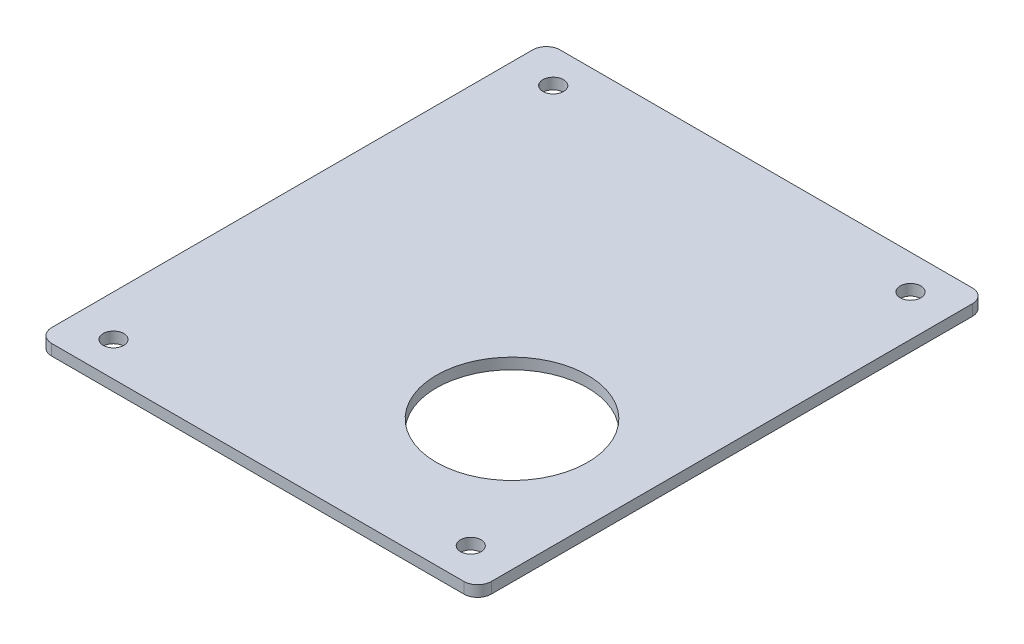
SolidWorks part; units mm, degrees
material "A-玻璃纤维"
ref_plane "前视基准面" through (0, 0, 0) normal (0, 0, 1) x (1, 0, 0)
ref_plane "上视基准面" through (0, 0, 0) normal (0, 1, 0) x (1, 0, 0)
ref_plane "右视基准面" through (0, 0, 0) normal (1, 0, 0) x (0, 0, -1)
other "Configuration Table"
sketch "草图1" plane through (0, 0, 0) normal (0, 1, 0) x (1, 0, 0)
  line L0 (0, 0) -> (0, 33.5742) construction
  line L1 (-32, -37) -> (32, -37)
  line L2 (-32, -37) -> (-32, 37)
  line L3 (-32, 37) -> (32, 37)
  line L4 (32, -37) -> (32, 37)
  line L5 (-32, -37) -> (32, 37) construction
  line L6 (-32, 37) -> (32, -37) construction
  line L7 (0, 0) -> (44.1006, 0) construction
  circle A0 centre (26, 32) radius 1.5
  circle A3 centre (-26, 32) radius 1.5
  circle A4 centre (13, -13) radius 11
  circle A5 centre (26, -32) radius 1.5
  circle A6 centre (-26, -32) radius 1.5
  point P0 (0, 0)
  dimension "D3" = 3
  dimension "D4" = 52
  dimension "D6" = 22
  dimension "D5" = 64
  dimension "D8" = 50
  dimension "D1" = 64
  dimension "D2" = 74
  dimension "D7" = 45
extrude "凸台-拉伸1" add sketch "草图1" along normal blind 1.6
fillet "圆角1" radius 2 4 edges at (-32, 0.8, -37) (-32, 0.8, 37) (32, 0.8, -37) (32, 0.8, 37)
